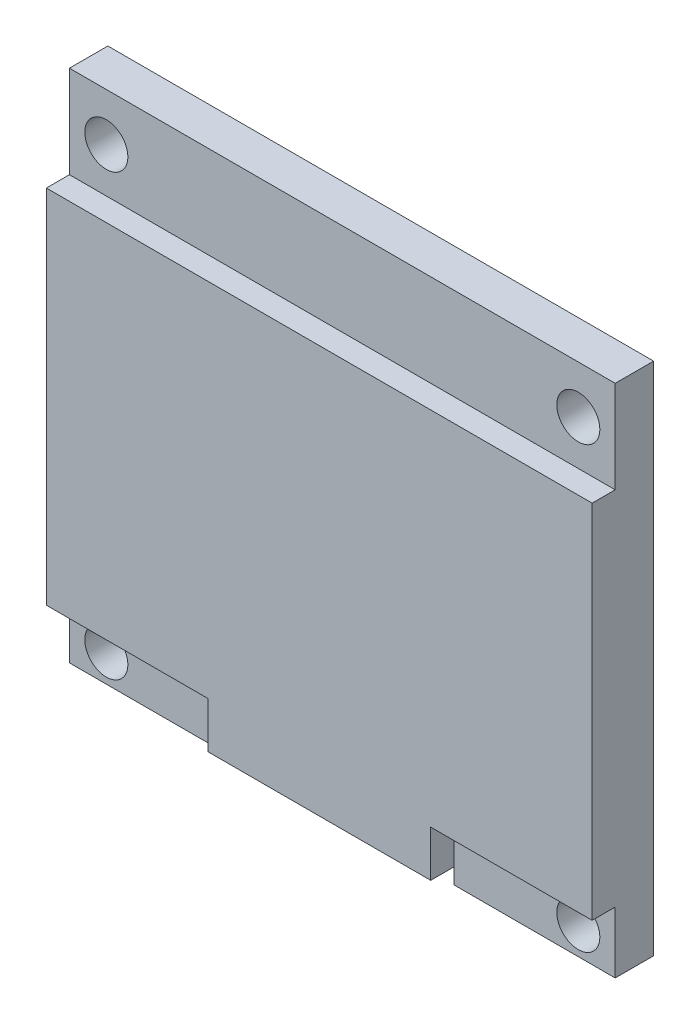
SolidWorks part; units mm, degrees
ref_plane "前视基准面" through (0, 0, 0) normal (0, 0, 1) x (1, 0, 0)
ref_plane "上视基准面" through (0, 0, 0) normal (0, 1, 0) x (1, 0, 0)
ref_plane "右视基准面" through (0, 0, 0) normal (1, 0, 0) x (0, 0, -1)
sketch "草图1" plane through (0, 0, 0) normal (0, 0, 1) x (1, 0, 0)
  line L1 (-17.75, 16.75) -> (17.75, 16.75)
  line L2 (-17.75, 16.75) -> (-17.75, -16.75)
  line L3 (-17.75, -16.75) -> (17.75, -16.75)
  line L4 (17.75, 16.75) -> (17.75, -16.75)
  line L5 (-17.75, 16.75) -> (17.75, -16.75) construction
  line L6 (-17.75, -16.75) -> (17.75, 16.75) construction
  point P0 (0, 0)
  dimension "D1" = 33.5
  dimension "D2" = 35.5
extrude "主板" add sketch "草图1" along normal blind 2.5
sketch "草图3" plane through (0, 0, 2.5) normal (0, 0, 1) x (1, 0, 0)
  line L0 (17.75, 16.75) -> (17.75, 10.75) construction
  line L2 (17.75, -16.75) -> (17.75, 16.75) construction
  line L3 (-17.75, -16.75) -> (-17.75, -12.75) construction
  line L4 (-17.75, 16.75) -> (-17.75, -16.75) construction
  line L5 (-17.75, -12.75) -> (-7.25, -12.75) construction
  line L6 (-17.75, -12.75) -> (17.75, -12.75)
  line L7 (-17.75, -12.75) -> (-17.75, 10.75)
  line L8 (-17.75, 10.75) -> (17.75, 10.75)
  line L9 (17.75, -12.75) -> (17.75, 10.75)
  line L10 (17.75, -16.75) -> (17.75, -15.75) construction
  line L11 (17.75, -15.75) -> (7.25, -15.75) construction
  line L13 (-7.25, -12.75) -> (7.25, -12.75)
  line L14 (-7.25, -12.75) -> (-7.25, -15.75)
  line L15 (-7.25, -15.75) -> (7.25, -15.75)
  line L16 (7.25, -12.75) -> (7.25, -15.75)
  line M9 (17.75, -16.75) -> (17.75, 16.75)
  line M11 (-17.75, 16.75) -> (-17.75, -16.75)
  dimension "D1" = 6
  dimension "D2" = 4
  dimension "D3" = 10.5
  dimension "D4" = 1
  dimension "D5" = 10.5
extrude "显示区域" add sketch "草图3" along normal blind 1.5 contours L8 L6 M11 M9 | L16 L6 L14 L15
sketch "草图4" plane through (0, 0, 2.5) normal (0, 0, 1) x (1, 0, 0)
  line L0 (7.25, -15.75) -> (7.25, -16.75) construction
  line L1 (-17.75, -16.75) -> (17.75, -16.75) construction
  line L3 (-7.25, -15.75) -> (7.25, -15.75)
  line L4 (-7.25, -15.75) -> (-7.25, -16.75)
  line L5 (-7.25, -16.75) -> (7.25, -16.75)
  line L6 (7.25, -15.75) -> (7.25, -16.75)
extrude "排线槽" cut sketch "草图4" against normal through all
sketch "草图5" plane through (0, 0, 2.5) normal (0, 0, 1) x (1, 0, 0)
  line L0 (17.75, 16.75) -> (17.75, 13.65) construction
  line L1 (17.75, 10.75) -> (17.75, 16.75) construction
  line L2 (17.75, 13.65) -> (15.35, 13.65) construction
  line L3 (0, 16.75) -> (0, 10.75) construction
  line L4 (17.75, 16.75) -> (-17.75, 16.75) construction
  line L5 (-17.75, 10.75) -> (17.75, 10.75) construction
  circle A0 centre (15.35, 13.65) radius 1.4
  circle A1 centre (-15.35, 13.65) radius 1.4
  dimension "D1" = 3.1
  dimension "D2" = 2.4
extrude "切除-拉伸2" cut sketch "草图5" against normal through all
sketch "草图6" plane through (0, 0, 2.5) normal (0, 0, 1) x (1, 0, 0)
  line L0 (17.75, -16.75) -> (15.35, -16.75) construction
  line L1 (7.25, -16.75) -> (17.75, -16.75) construction
  line L2 (15.35, -16.75) -> (15.35, -14.95) construction
  circle A0 centre (15.35, -14.95) radius 1.4
  dimension "D1" = 2.4
  dimension "D2" = 1.8
extrude "切除-拉伸3" cut sketch "草图6" against normal through all
ref_plane "基准面4" through (0, 0, 0) normal (1, 0, 0) x (0, 0, -1)
mirror "镜向1" about plane through (0, 0, 0) normal (1, 0, 0) of "切除-拉伸3"
